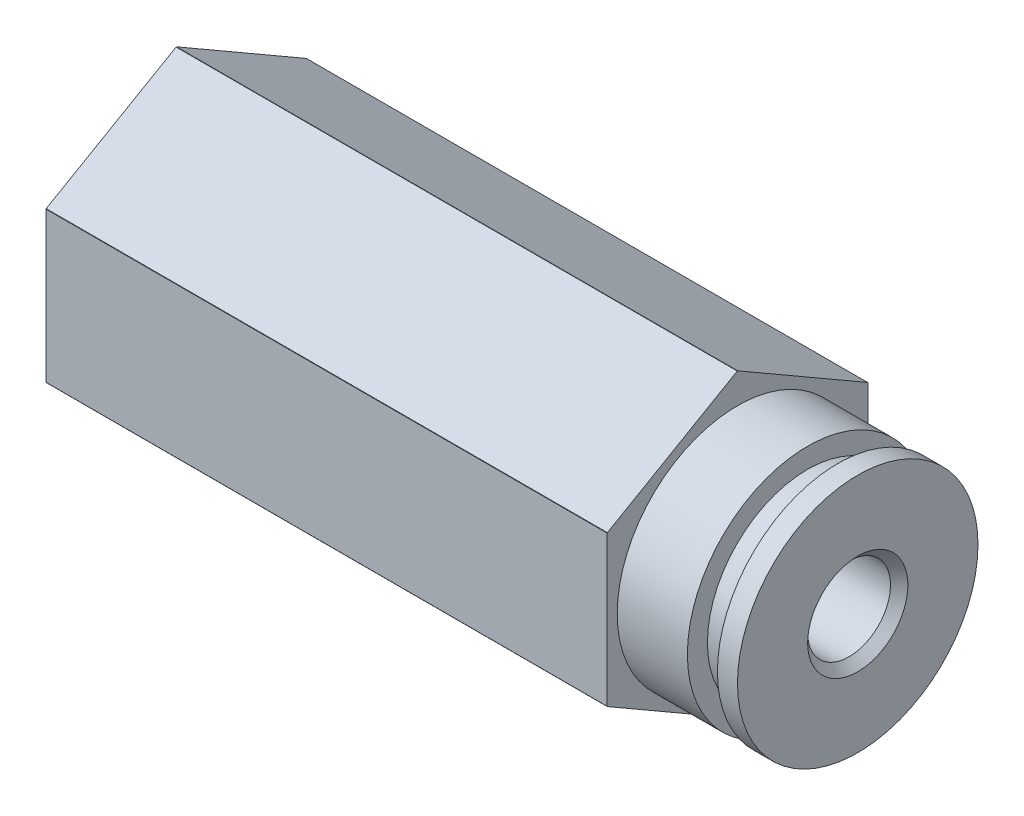
SolidWorks part; units mm, degrees
material "6061 合金"
ref_plane "前视基准面" through (0, 0, 0) normal (0, 0, 1) x (1, 0, 0)
ref_plane "上视基准面" through (0, 0, 0) normal (0, 1, 0) x (1, 0, 0)
ref_plane "右视基准面" through (0, 0, 0) normal (1, 0, 0) x (0, 0, -1)
ref_plane "基准面1" through (0, 0, 0) normal (0, 0, 1) x (1, 0, 0)
sketch "草图1" plane through (0, 0, 0) normal (0, 0, 1) x (1, 0, 0)
  line L0 (0, 0) -> (0, 7.5)
  line L1 (0, 7.5) -> (28, 7.5)
  line L2 (28, 7.5) -> (28, 6)
  line L3 (28, 6) -> (31.5, 6)
  line L4 (31.5, 6) -> (31.5, 5)
  line L5 (31.5, 5) -> (33, 5)
  line L6 (33, 5) -> (33, 6)
  line L7 (33, 6) -> (34, 6)
  line L8 (34, 6) -> (34, 0)
  line L9 (34, 0) -> (0, 0)
  line L10 (34, 0) -> (0, 0) construction
revolve "旋转1" add sketch "草图1" angle 360 about L10
cosmetic thread "装饰螺纹线1" parameters "D1"=28, "D2"=13.16
ref_plane "基准面2" through (0, 0, 0) normal (0, 0, 1) x (1, 0, 0)
sketch "草图2" plane through (0, 0, 0) normal (0, 0, 1) x (1, 0, 0)
  line L0 (0, 0) -> (0, 2.5)
  line L1 (0, 2.5) -> (6.5, 2.5)
  line L2 (6.5, 2.5) -> (6.5, 5)
  line L3 (6.5, 5) -> (23.5, 5)
  line L4 (23.5, 5) -> (23.5, 0)
  line L5 (23.5, 0) -> (0, 0)
  line L6 (23.5, 0) -> (0, 0) construction
revolve "切除-旋转1" cut sketch "草图2" angle 360 about L6
ref_plane "基准面3" through (0, 0, 0) normal (0, 0, 1) x (1, 0, 0)
sketch "草图3" plane through (0, 0, 0) normal (0, 0, 1) x (1, 0, 0)
  line L0 (27.8066, 0) -> (29, 2.067)
  line L1 (29, 2.067) -> (33.567, 2.067)
  line L2 (33.567, 2.067) -> (34, 2.5)
  line L3 (34, 2.5) -> (34, 0)
  line L4 (34, 0) -> (27.8066, 0)
  line L5 (34, 0) -> (27.8066, 0) construction
revolve "切除-旋转2" cut sketch "草图3" angle 360 about L5
cosmetic thread "装饰螺纹线2" parameters "D1"=5, "D2"=5
ref_plane "基准面4" through (0, 0, 0) normal (1, 0, 0) x (0, 0, -1)
sketch "草图4" plane through (0, 0, 0) normal (1, 0, 0) x (0, 0, -1)
  line L0 (-6.5, -3.7528) -> (0, -7.5056)
  line L1 (0, -7.5056) -> (6.5, -3.7528)
  line L2 (6.5, -3.7528) -> (6.5, 3.7528)
  line L3 (6.5, 3.7528) -> (0, 7.5056)
  line L4 (0, 7.5056) -> (-6.5, 3.7528)
  line L5 (-6.5, 3.7528) -> (-6.5, -3.7528)
  circle A0 centre (0, 0) radius 23.9588
extrude "切除-拉伸1" cut sketch "草图4" along normal blind 28
ref_plane "基准面5" through (0, 0, 0) normal (1, 0, 0) x (0, 0, -1)
sketch "草图5" plane through (0, 0, 0) normal (1, 0, 0) x (0, 0, -1)
  circle A0 centre (0, 4) radius 0.4
extrude "切除-拉伸2" cut sketch "草图5" along normal blind 3
